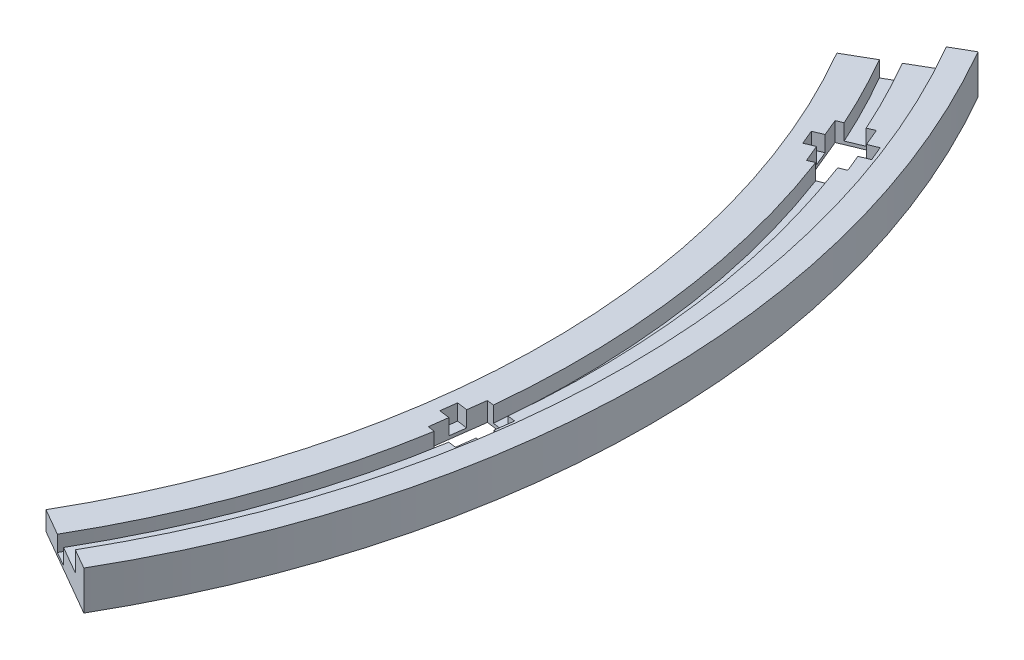
SolidWorks part; units mm, degrees
ref_plane "Ebene vorne" through (0, 0, 0) normal (0, 0, 1) x (1, 0, 0)
ref_plane "Ebene oben" through (0, 0, 0) normal (0, 1, 0) x (1, 0, 0)
ref_plane "Ebene rechts" through (0, 0, 0) normal (1, 0, 0) x (0, 0, -1)
sketch "Skizze1" plane through (0, 0, 0) normal (0, 1, 0) x (1, 0, 0)
  line L0 (0, 0) -> (169.6, 0) construction
  line L1 (146.8779, 84.8) -> (129.9038, 75)
  line L2 (129.9038, -75) -> (146.8779, -84.8)
  line L3 (0, 0) -> (146.8779, 84.8) construction
  line L4 (0, 0) -> (146.8779, -84.8) construction
  arc A0 (129.9038, -75) -> (129.9038, 75) centre (0, 0) ccw
  arc A1 (146.8779, -84.8) -> (146.8779, 84.8) centre (0, 0) ccw
  dimension "D1" = 169.6
  dimension "D2" = 150
  dimension "D5" = 30
  dimension "D6" = 30
extrude "Aufsatz-Linear austragen1" add sketch "Skizze1" along normal blind 3.6
sketch "Skizze2" plane through (0, 3.6, 0) normal (0, 1, 0) x (1, 0, 0)
  line L0 (129.9038, -75) -> (146.8779, -84.8) construction
  line L1 (146.8779, 84.8) -> (129.9038, 75) construction
  line L2 (135.0134, 77.95) -> (137.7846, 79.55)
  line L5 (135.0134, -77.95) -> (137.7846, -79.55)
  arc A0 (135.0134, -77.95) -> (135.0134, 77.95) centre (0, 0) ccw
  arc A1 (137.7846, -79.55) -> (137.7846, 79.55) centre (0, 0) ccw
  dimension "D4" = 5.9
  dimension "D3" = 3.2
extrude "Schnitt-Linear austragen1" cut sketch "Skizze2" against normal blind 3
sketch "Skizze3" plane through (0, 3.6, 0) normal (0, 1, 0) x (1, 0, 0)
  line L0 (137.7846, -79.55) -> (146.8779, -84.8) construction
  line L1 (146.8779, 84.8) -> (137.7846, 79.55) construction
  line L2 (0, 0) -> (145.511, 60.2726) construction
  line L3 (0, 0) -> (169.6, 0) construction
  line L4 (0, 0) -> (156.1526, -20.5579) construction
  line L5 (140.826, 63.744) -> (146.3692, 66.0401)
  line L6 (146.3692, 66.0401) -> (150.1961, 56.8013)
  line L7 (150.1961, 56.8013) -> (144.6528, 54.5052)
  line L8 (144.6528, 54.5052) -> (140.826, 63.744)
  line L9 (144.6528, 54.5052) -> (146.3692, 66.0401) construction
  line L14 (153.8309, -15.2091) -> (159.7795, -15.9922)
  line L15 (159.7795, -15.9922) -> (158.4743, -25.9067)
  line L16 (158.4743, -25.9067) -> (152.5256, -25.1235)
  line L17 (152.5256, -25.1235) -> (153.8309, -15.2091)
  line L18 (152.5256, -25.1235) -> (159.7795, -15.9922) construction
  arc A0 (136.399, -78.75) -> (136.399, 78.75) centre (0, 0) ccw construction
  arc A2 (146.8779, -84.8) -> (146.8779, 84.8) centre (0, 0) ccw construction
  point P8 (156.1526, -20.5579)
  point P18 (145.511, 60.2726)
  dimension "D1" = 157.5
  dimension "D3" = 22.5
  dimension "D4" = 30
  dimension "D5" = 10
  dimension "D6" = 6
extrude "Schnitt-Linear austragen2" cut sketch "Skizze3" against normal through all
sketch "Skizze4" plane through (0, 3.6, 0) normal (0, 1, 0) x (1, 0, 0)
  line L0 (140.3176, 59.745) -> (149.5564, 63.5719)
  line L1 (149.5564, 63.5719) -> (150.7044, 60.8002)
  line L2 (150.7044, 60.8002) -> (141.4657, 56.9734)
  line L3 (141.4657, 56.9734) -> (140.3176, 59.745)
  line L8 (142.0453, 64.2491) -> (140.826, 63.744) construction
  line L9 (140.826, 63.744) -> (144.6528, 54.5052) construction
  line L12 (141.4657, 56.9734) -> (149.5564, 63.5719) construction
  line L13 (144.6528, 54.5052) -> (146.3692, 66.0401) construction
  line L14 (151.3911, -18.4181) -> (161.3056, -19.7233)
  line L16 (161.3056, -19.7233) -> (160.914, -22.6977)
  line L17 (160.914, -22.6977) -> (150.9996, -21.3924)
  line L18 (150.9996, -21.3924) -> (151.3911, -18.4181)
  line L19 (158.3136, -15.7992) -> (155.1394, -15.3813) construction
  line L20 (153.8309, -15.2091) -> (152.5256, -25.1235) construction
  line L21 (152.5256, -25.1235) -> (159.7795, -15.9922) construction
  line L22 (151.3911, -18.4181) -> (160.914, -22.6977) construction
  point P20 (145.511, 60.2726)
  point P21 (145.511, 60.2726)
  point P24 (156.1526, -20.5579)
  point P25 (156.1526, -20.5579)
  dimension "D1" = 10
  dimension "D2" = 3
extrude "Schnitt-Linear austragen3" cut sketch "Skizze4" against normal blind 3
sketch "Skizze5" plane through (0, 3.6, 0) normal (0, 1, 0) x (1, 0, 0)
  line L0 (143.0674, 82.6) -> (146.8779, 84.8)
  line L1 (143.0674, -82.6) -> (146.8779, -84.8)
  line L2 (137.7846, -79.55) -> (146.8779, -84.8) construction
  line L3 (146.8779, 84.8) -> (137.7846, 79.55) construction
  arc A0 (146.8779, -84.8) -> (146.8779, 84.8) centre (0, 0) ccw
  arc A1 (143.0674, -82.6) -> (143.0674, 82.6) centre (0, 0) ccw
  dimension "D1" = 4.4
extrude "Aufsatz-Linear austragen2" add sketch "Skizze5" along normal blind 3.8
equation "\"D6@Skizze1\"=\"D5@Skizze1\""
